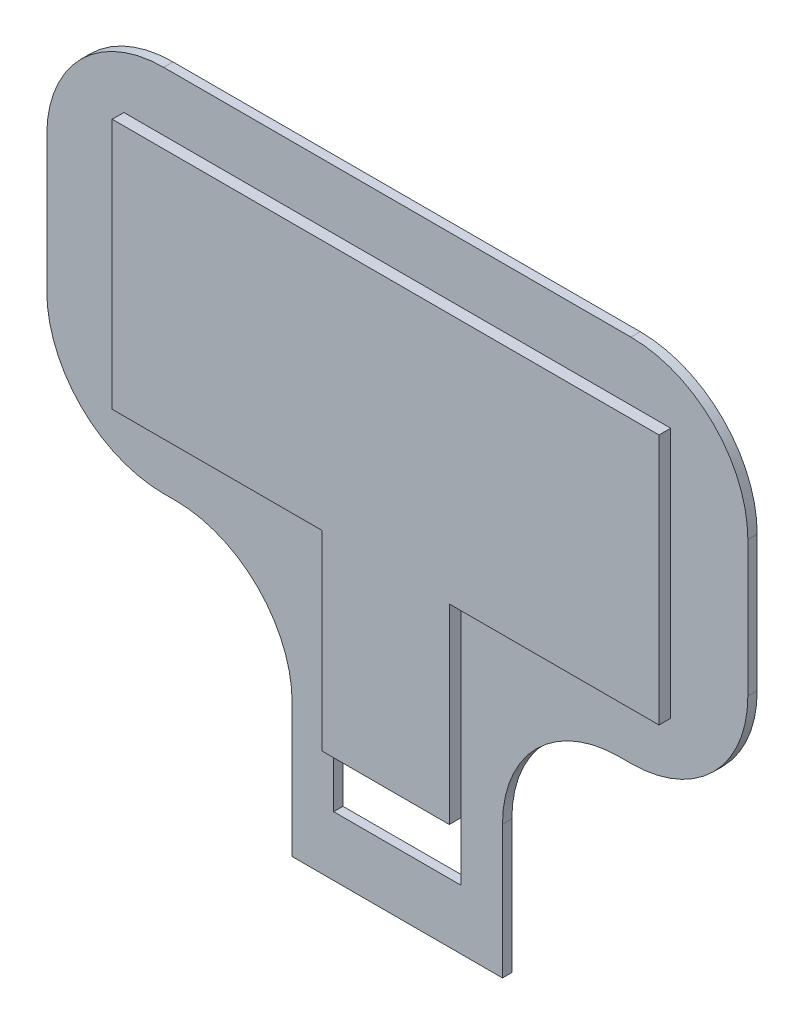
SolidWorks part; units mm, degrees
ref_plane "Front Plane" through (0, 0, 0) normal (0, 0, 1) x (1, 0, 0)
ref_plane "Top Plane" through (0, 0, 0) normal (0, 1, 0) x (1, 0, 0)
ref_plane "Right Plane" through (0, 0, 0) normal (1, 0, 0) x (0, 0, -1)
sketch "Sketch1" plane through (0, 0, 0) normal (0, 0, 1) x (1, 0, 0)
  line L1 (0, 0) -> (60, 0)
  line L2 (0, 0) -> (0, 53)
  line L3 (0, 53) -> (60, 53)
  line L4 (60, 0) -> (60, 53)
  dimension "D1" = 53
  dimension "D2" = 60
extrude "Boss-Extrude1" add sketch "Sketch1" along normal blind 0.8
sketch "Sketch2" plane through (0, 0, 0.8) normal (0, 0, 1) x (1, 0, 0)
  line L0 (60, 0) -> (60, 53) construction
  line L1 (10, 53) -> (50, 53)
  line L2 (0, 43) -> (0, 31.4)
  line L3 (10, 21.4) -> (11, 21.4)
  line L4 (60, 43) -> (60, 31.4)
  line L5 (0, 0) -> (60, 0) construction
  line L6 (21, 0) -> (39, 0)
  line L7 (21, 0) -> (21, 11.4)
  line L9 (39, 0) -> (39, 11.4)
  line L11 (49, 21.4) -> (50, 21.4)
  line L13 (0, 53) -> (60, 53)
  line L14 (0, 53) -> (0, 0)
  line L15 (0, 0) -> (60, 0)
  line L16 (60, 53) -> (60, 0)
  arc A0 (0, 31.4) -> (10, 21.4) centre (10, 31.4) ccw
  arc A1 (10, 53) -> (0, 43) centre (10, 43) ccw
  arc A2 (50, 53) -> (60, 43) centre (50, 43) cw
  arc A3 (50, 21.4) -> (60, 31.4) centre (50, 31.4) ccw
  arc A4 (21, 11.4) -> (11, 21.4) centre (11, 11.4) ccw
  arc A5 (49, 21.4) -> (39, 11.4) centre (49, 11.4) ccw
  point P13 (30, 0)
  point P14 (30, 53)
  point P17 (0, 21.4)
  point P20 (0, 53)
  point P25 (60, 21.4)
  point P30 (39, 21.4)
  line M5 (0, 53) -> (0, 0)
  line M6 (0, 0) -> (60, 0)
  line M7 (60, 0) -> (60, 53)
  line M8 (60, 53) -> (0, 53)
  dimension "D4" = 10
  dimension "D1" = 18
  dimension "D3" = 31.6
extrude "Cut-Extrude2" cut sketch "Sketch2" against normal blind 0.8 contours A1 M8 M5 | L7 A4 L3 A0 M5 M6 | L11 A5 L9 A3 M6 M7 | A2 M8 M7
sketch "Sketch3" plane through (0, 0, 0.8) normal (0, 0, 1) x (1, 0, 0)
  line L0 (60, 31.4) -> (60, 43) construction
  line L1 (24.55, 5.1) -> (35.45, 5.1)
  line L2 (24.55, 5.1) -> (24.55, 26.45)
  line L3 (24.55, 26.45) -> (35.45, 26.45)
  line L4 (35.45, 5.1) -> (35.45, 26.45)
  line L6 (6.6, 47.95) -> (53.4, 47.95)
  line L7 (6.6, 47.95) -> (6.6, 26.45)
  line L8 (6.6, 26.45) -> (53.4, 26.45)
  line L9 (53.4, 47.95) -> (53.4, 26.45)
  line L10 (50, 53) -> (10, 53) construction
  line L12 (21, 0) -> (39, 0) construction
  point P10 (30, 26.45)
  point P14 (60, 37.2)
  point P15 (53.4, 37.2)
  point P18 (30, 53)
  point P19 (30, 47.95)
  line M18 (21, 0) -> (39, 0)
  dimension "D1" = 10.9
  dimension "D3" = 21.5
  dimension "D4" = 46.8
  dimension "D7" = 0
  dimension "D8" = 5.1
extrude "Boss-Extrude2" add sketch "Sketch3" along normal blind 1 contours L9 L6 L7 L8 L3 | L4 L3 L2 M18
sketch "Sketch4" plane through (0, 0, 1.8) normal (0, 0, 1) x (1, 0, 0)
  line L0 (35.45, 5.1) -> (35.45, 26.45) construction
  line L1 (24.55, 5.1) -> (35.45, 5.1)
  line L2 (24.55, 5.1) -> (24.55, 10.1)
  line L3 (24.55, 10.1) -> (35.45, 10.1)
  line L4 (35.45, 5.1) -> (35.45, 10.1)
  dimension "D1" = 5
extrude "Cut-Extrude3" cut sketch "Sketch4" against normal blind 10
